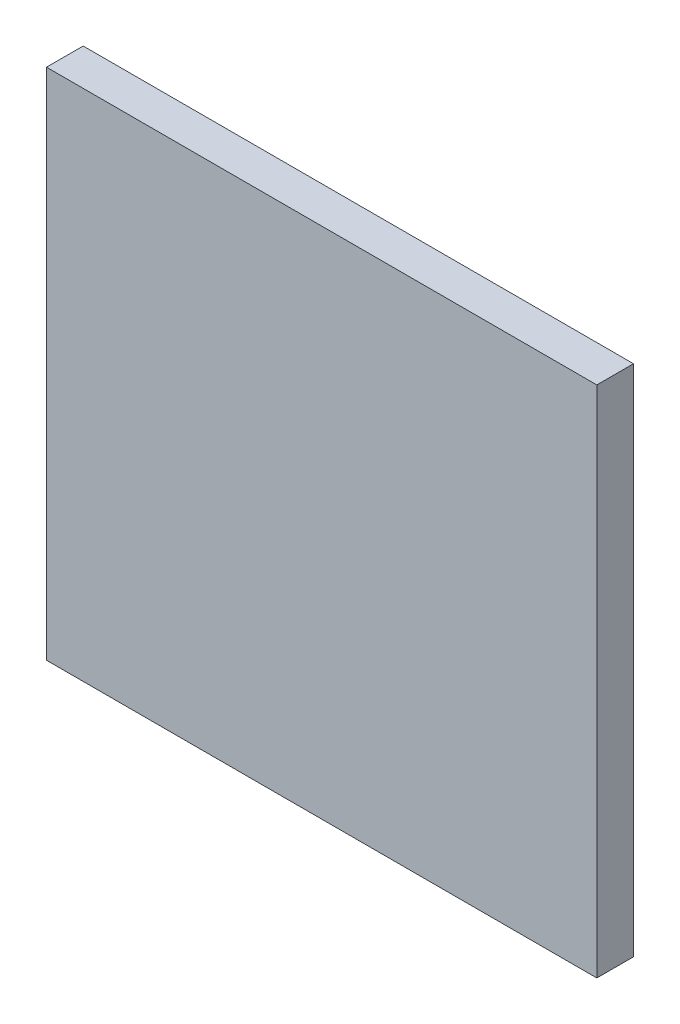
SolidWorks part; units mm, degrees
ref_plane "前视基准面" through (0, 0, 0) normal (0, 0, 1) x (1, 0, 0)
ref_plane "上视基准面" through (0, 0, 0) normal (0, 1, 0) x (1, 0, 0)
ref_plane "右视基准面" through (0, 0, 0) normal (1, 0, 0) x (0, 0, -1)
sketch "草图1" plane through (0, 0, 0) normal (0, 0, 1) x (1, 0, 0)
  line L1 (-150, 140) -> (150, 140)
  line L2 (-150, 140) -> (-150, -140)
  line L3 (-150, -140) -> (150, -140)
  line L4 (150, 140) -> (150, -140)
  line L5 (-150, 140) -> (150, -140) construction
  line L6 (-150, -140) -> (150, 140) construction
  point P0 (0, 0)
  dimension "D1" = 300
  dimension "D2" = 280
extrude "凸台-拉伸1" add sketch "草图1" along normal mid plane 20
sketch "草图2" plane through (-150, 0, 0) normal (-1, 0, 0) x (0, 0, 1)
  line L1 (-10, -140) -> (-160, -140)
  line L2 (-10, -140) -> (-10, -110)
  line L3 (-10, -110) -> (-160, -110)
  line L4 (-160, -140) -> (-160, -110)
  dimension "D1" = 30
  dimension "D2" = 150
extrude "凸台-拉伸2" [suppressed] add sketch "草图2" against normal up to surface (300 mm away)
sketch "草图3" [suppressed] plane through (-150, 0, 0) normal (-1, 0, 0) x (0, 0, 1)
  line L0 (-130, -170) -> (-130, -140)
  line L1 (-10, -170) -> (-160, -170) construction
  line L2 (-130, -140) -> (-40, 80)
  line L3 (-40, 80) -> (-10, 80)
  line L4 (-10, 200) -> (-10, -170) construction
  line L5 (-10, 80) -> (-10, -170)
  line L6 (-10, -170) -> (-130, -170)
  line L7 (-160, -170) -> (-160, -200) construction
  dimension "D1" = 30
  dimension "D2" = 30
  dimension "D3" = 30
  dimension "D4" = 250
extrude "凸台-拉伸3" [suppressed] add sketch "草图3" against normal blind 20 separate body
mirror "镜向1" [suppressed] about plane through (0, 0, 0) normal (1, 0, 0)
sketch "草图4" plane through (0, 0, 10) normal (0, 0, 1) x (1, 0, 0)
  line L0 (0, 140) -> (0, -140) construction
  line L1 (150, 140) -> (-150, 140) construction
  line L2 (-150, -140) -> (150, -140) construction
  line L4 (40, 105) -> (-40, 105)
  line L5 (40, 105) -> (40, -75)
  line L6 (40, -75) -> (-40, -75)
  line L7 (-40, 105) -> (-40, -75)
  dimension "D1" = 80
  dimension "D2" = 35
  dimension "D3" = 180
extrude "切除-拉伸1" [suppressed] cut sketch "草图4" against normal through all
fillet "圆角1" [suppressed] radius 10
equation "\"零件重量\"= \"SW-质量\""
